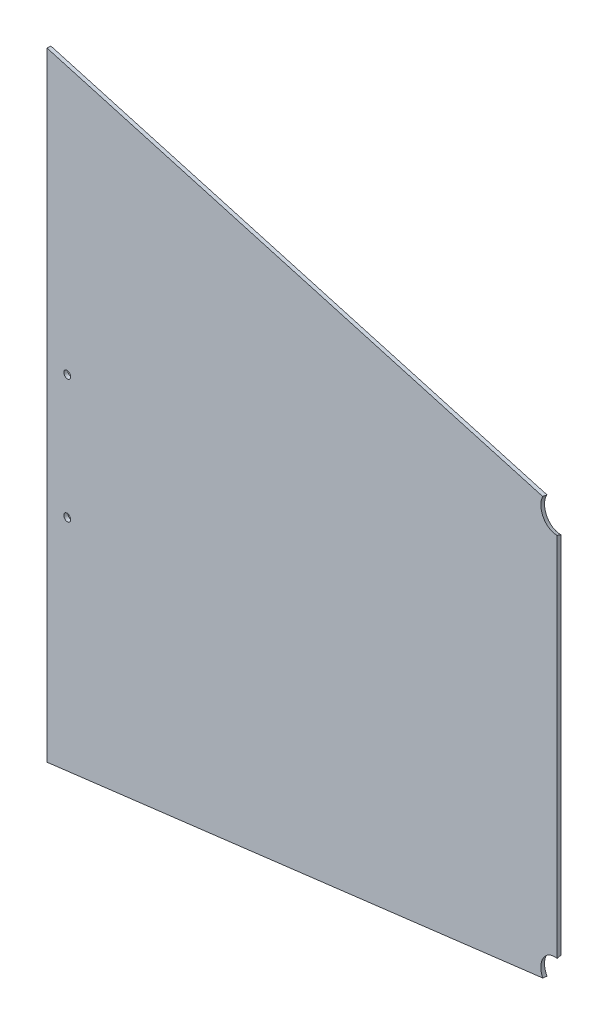
SolidWorks part; units mm, degrees
material "6061-T6 (SS)"
ref_plane "X-Y Datum" through (0, 0, 0) normal (0, 0, 1) x (1, 0, 0)
ref_plane "X-Z Datum" through (0, 0, 0) normal (0, 1, 0) x (1, 0, 0)
ref_plane "Y-Z Datum" through (0, 0, 0) normal (1, 0, 0) x (0, 0, -1)
ref_plane "Plane1" through (1.0099, 0, -13.5995) normal (0.0741, 0, -0.9973) x (-0.9973, 0, -0.0741)
ref_plane "Plane2" through (1.9503, 0, -26.2646) normal (0.0741, 0, -0.9973) x (-0.9973, 0, -0.0741)
sketch "Sketch1" plane through (1.9503, 0, -26.2646) normal (0.0741, 0, -0.9973) x (-0.9973, 0, -0.0741)
  line L0 (-183.6444, -298.45) -> (-183.6444, 298.45) construction
  line L1 (-183.6444, -298.45) -> (-826.7602, -177.8) construction
  line L2 (-826.7602, -177.8) -> (-826.7602, 177.8) construction
  line L3 (-826.7602, 177.8) -> (-183.6444, 298.45) construction
  line L4 (-183.6444, -298.45) -> (-183.6444, 298.45)
  line L5 (-183.6444, -298.45) -> (-826.7602, -177.8)
  line L6 (-826.7602, -177.8) -> (-826.7602, 177.8)
  line L7 (-826.7602, 177.8) -> (-183.6444, 298.45)
extrude "Boss-Extrude1" add sketch "Sketch1" along normal blind 3.175
ref_plane "Plane3" through (825.5, 212.9428, 150.983) normal (0, 0.3219, 0.9468) x (1, 0, 0)
sketch "Sketch2" plane through (825.5, 212.9428, 150.983) normal (0, 0.3219, 0.9468) x (1, 0, 0)
  circle A0 centre (0, 0) radius 14.2875
  dimension "D1" = 28.575
extrude "Cut-Extrude1" cut sketch "Sketch2" against normal through all contours A0
mirror "Mirror1" about plane through (0, 0, 0) normal (0, 1, 0) of "Cut-Extrude1"
sketch "Sketch3" plane through (1.9503, 0, -26.2646) normal (-0.0741, 0, 0.9973) x (0.9973, 0, 0.0741)
  line L0 (348.7444, 267.4769) -> (348.7444, -267.4769)
  line L1 (813.2196, -180.3402) -> (183.6444, -298.45) construction
  line L2 (183.6444, -298.45) -> (183.6444, 298.45) construction
  line L3 (183.6444, 298.45) -> (813.2196, 180.3402) construction
  point P5 (348.7444, 0)
  point P7 (348.7444, 267.4769)
  line M2 (183.6444, -298.45) -> (813.2196, -180.3402)
  line M6 (813.2196, 180.3402) -> (183.6444, 298.45)
  line M7 (183.6444, 298.45) -> (183.6444, -298.45)
  dimension "D1" = 165.1
extrude "Cut-Extrude2" cut sketch "Sketch3" against normal through all contours L0 M6 M7 M2
sketch "Sketch4" plane through (2.1855, 0, -29.4309) normal (0.0741, 0, -0.9973) x (-0.9973, 0, -0.0741)
  line L0 (-336.0444, 33) -> (-367.7944, 33) construction
  line L1 (-336.0444, -74) -> (-367.7944, -74) construction
  line L2 (-348.7444, 267.4769) -> (-348.7444, -267.4769) construction
  line L3 (-348.7444, 267.4769) -> (-348.7444, -267.4769)
  circle A0 centre (-367.7944, 33) radius 3.175
  circle A1 centre (-367.7944, -74) radius 3.175
  point P0 (-336.0444, 33)
  point P1 (-336.0444, -74)
  point P2 (-336.0444, -74)
  point P11 (0, 0)
  dimension "D1" = 6.35
  dimension "D2" = 19.05
extrude "Cut-Extrude3" cut sketch "Sketch4" against normal through all contours A0 | A1
